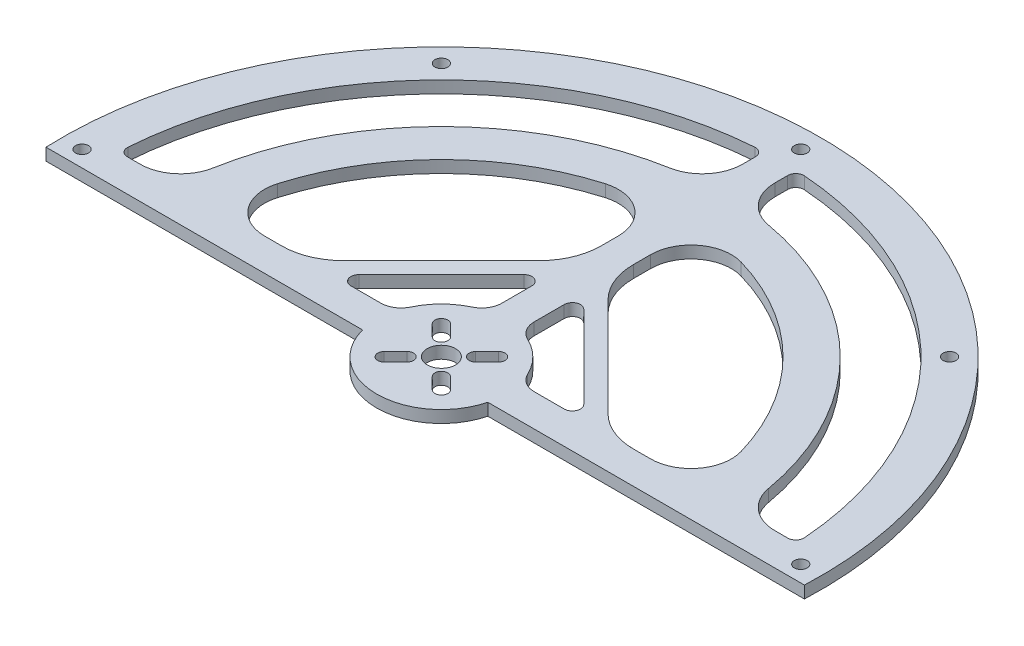
SolidWorks part; units mm, degrees
ref_plane "前视基准面" through (0, 0, 0) normal (0, 0, 1) x (1, 0, 0)
ref_plane "上视基准面" through (0, 0, 0) normal (0, 1, 0) x (1, 0, 0)
ref_plane "右视基准面" through (0, 0, 0) normal (1, 0, 0) x (0, 0, -1)
other "Configuration Table"
sketch "草图1" plane through (0, 0, 0) normal (0, 1, 0) x (1, 0, 0)
  line L0 (0, 0) -> (93.9, 0) construction
  line L15 (46.95, 4) -> (46.95, -4) construction
  line L16 (46.95, 4) -> (47.7604, 4)
  line L17 (46.95, -4) -> (83.8046, -4)
  line L18 (46.95, 4) -> (43.5008, 4)
  line L19 (46.95, -4) -> (15.4919, -4)
  line L20 (-46.95, -4) -> (-15.4919, -4)
  line L21 (-46.95, 4) -> (-43.5008, 4)
  line L22 (-46.95, 4) -> (-47.7604, 4)
  line L23 (-46.95, -4) -> (-83.8046, -4)
  line L24 (-78.5319, 4) -> (-81.6799, 4)
  line L25 (83.8046, -4) -> (93.8148, -4)
  line L26 (-4, 78.5319) -> (-4, 81.6799)
  line L27 (-83.8046, -4) -> (-93.8148, -4)
  line L28 (-4, 46.95) -> (-4, 43.5008)
  line L29 (4, 46.95) -> (4, 43.5008)
  line L30 (-4, 46.95) -> (-4, 47.7604)
  line L31 (4, 46.95) -> (4, 47.7604)
  line L32 (4, 78.5319) -> (4, 81.6799)
  line L33 (-27.8068, 7.4142) -> (-7.4142, 27.8068)
  line L34 (78.5319, 4) -> (81.6799, 4)
  line L35 (4, 83.8046) -> (4, 88.81) [skipped]
  line L36 (27.8068, 7.4142) -> (7.4142, 27.8068)
  line L38 (-32.7805, 8.4405) -> (-8.4405, 32.7805)
  line L40 (32.7805, 8.4405) -> (8.4405, 32.7805)
  line L41 (-4, 26.3925) -> (-4, 18.9737)
  line L42 (4, 26.3925) -> (4, 18.9737)
  line L43 (26.3925, 4) -> (18.9737, 4)
  line L44 (-26.3925, 4) -> (-18.9737, 4)
  line L45 (7.0711, -7.0711) -> (4.2426, -4.2426) construction
  line L46 (5.9397, -8.2024) -> (3.1113, -5.374)
  line L47 (8.2024, -5.9397) -> (5.374, -3.1113)
  line L51 (-7.0711, -7.0711) -> (-4.2426, -4.2426) construction
  line L52 (-8.2024, -5.9397) -> (-5.374, -3.1113)
  line L53 (-5.9397, -8.2024) -> (-3.1113, -5.374)
  line L57 (-7.0711, 7.0711) -> (-4.2426, 4.2426) construction
  line L58 (-5.9397, 8.2024) -> (-3.1113, 5.374)
  line L59 (-8.2024, 5.9397) -> (-5.374, 3.1113)
  line L63 (7.0711, 7.0711) -> (4.2426, 4.2426) construction
  line L64 (8.2024, 5.9397) -> (5.374, 3.1113)
  line L65 (5.9397, 8.2024) -> (3.1113, 5.374)
  arc A2 (64.6464, -4) -> (-64.6464, -4) centre (0, 0) ccw construction
  arc A3 (88.81, -4) -> (-88.81, -4) centre (0, 0) ccw construction
  arc A7 (93.8148, -4) -> (-93.8148, -4) centre (0, 0) ccw
  arc A8 (-15.4919, -4) -> (15.4919, -4) centre (0, 0) ccw
  circle A9 centre (0, 0) radius 8 construction
  arc A20 (14.4561, 6.8571) -> (6.8571, 14.4561) centre (0, 0) ccw
  arc A21 (57.3566, 16.8129) -> (16.8129, 57.3566) centre (0, 0) ccw
  arc A22 (68.6871, 12.245) -> (12.245, 68.6871) centre (0, 0) ccw
  arc A23 (83.6745, 6.1465) -> (6.1465, 83.6745) centre (0, 0) ccw
  arc A24 (-6.1465, 83.6745) -> (-83.6745, 6.1465) centre (0, 0) ccw
  arc A25 (-12.245, 68.6871) -> (-68.6871, 12.245) centre (0, 0) ccw
  arc A26 (-16.8129, 57.3566) -> (-57.3566, 16.8129) centre (0, 0) ccw
  arc A27 (-6.8571, 14.4561) -> (-14.4561, 6.8571) centre (0, 0) ccw
  circle A28 centre (88.9, 0) radius 1.6
  circle A32 centre (-88.9, 0) radius 1.6
  circle A33 centre (-62.8618, 62.8618) radius 1.6
  circle A34 centre (0, 88.9) radius 1.6
  circle A35 centre (62.8618, 62.8618) radius 1.6
  arc A36 (5.9397, -8.2024) -> (8.2024, -5.9397) centre (7.0711, -7.0711) ccw
  arc A37 (5.374, -3.1113) -> (3.1113, -5.374) centre (4.2426, -4.2426) ccw
  arc A40 (-8.2024, -5.9397) -> (-5.9397, -8.2024) centre (-7.0711, -7.0711) ccw
  arc A41 (-3.1113, -5.374) -> (-5.374, -3.1113) centre (-4.2426, -4.2426) ccw
  arc A44 (-5.9397, 8.2024) -> (-8.2024, 5.9397) centre (-7.0711, 7.0711) ccw
  arc A45 (-5.374, 3.1113) -> (-3.1113, 5.374) centre (-4.2426, 4.2426) ccw
  arc A48 (8.2024, 5.9397) -> (5.9397, 8.2024) centre (7.0711, 7.0711) ccw
  arc A49 (3.1113, 5.374) -> (5.374, 3.1113) centre (4.2426, 4.2426) ccw
  arc A50 (16.8129, 57.3566) -> (4, 47.7604) centre (14, 47.7604) ccw
  arc A51 (-4, 47.7604) -> (-16.8129, 57.3566) centre (-14, 47.7604) ccw
  arc A52 (57.3566, 16.8129) -> (47.7604, 4) centre (47.7604, 14) cw
  arc A53 (-47.7604, 4) -> (-57.3566, 16.8129) centre (-47.7604, 14) cw
  arc A54 (8.4405, 32.7805) -> (4, 43.5008) centre (19.1608, 43.5008) cw
  arc A55 (43.5008, 4) -> (32.7805, 8.4405) centre (43.5008, 19.1608) cw
  arc A56 (-8.4405, 32.7805) -> (-4, 43.5008) centre (-19.1608, 43.5008) ccw
  arc A57 (-32.7805, 8.4405) -> (-43.5008, 4) centre (-43.5008, 19.1608) cw
  arc A58 (78.5319, 4) -> (68.6871, 12.245) centre (78.5319, 14) cw
  arc A59 (4, 78.5319) -> (12.245, 68.6871) centre (14, 78.5319) ccw
  arc A60 (-4, 78.5319) -> (-12.245, 68.6871) centre (-14, 78.5319) cw
  arc A61 (-68.6871, 12.245) -> (-78.5319, 4) centre (-78.5319, 14) cw
  arc A62 (-81.6799, 4) -> (-83.6745, 6.1465) centre (-81.6799, 6) cw
  arc A63 (-4, 81.6799) -> (-6.1465, 83.6745) centre (-6, 81.6799) ccw
  arc A64 (4, 81.6799) -> (6.1465, 83.6745) centre (6, 81.6799) cw
  arc A65 (83.6745, 6.1465) -> (81.6799, 4) centre (81.6799, 6) cw
  arc A66 (-6.8571, 14.4561) -> (-4, 18.9737) centre (-9, 18.9737) ccw
  arc A67 (6.8571, 14.4561) -> (4, 18.9737) centre (9, 18.9737) cw
  arc A68 (18.9737, 4) -> (14.4561, 6.8571) centre (18.9737, 9) cw
  arc A69 (-14.4561, 6.8571) -> (-18.9737, 4) centre (-18.9737, 9) cw
  arc A70 (26.3925, 4) -> (27.8068, 7.4142) centre (26.3925, 6) ccw
  arc A71 (-26.3925, 4) -> (-27.8068, 7.4142) centre (-26.3925, 6) cw
  arc A72 (-4, 26.3925) -> (-7.4142, 27.8068) centre (-6, 26.3925) ccw
  arc A73 (7.4142, 27.8068) -> (4, 26.3925) centre (6, 26.3925) ccw
  circle A74 centre (0, 0) radius 3.5
  point P16 (0, 8)
  point P31 (0, -8)
  point P32 (37.221, 4)
  point P38 (-8, 0)
  point P40 (-37.221, 4)
  point P43 (0, 0)
  point P44 (46.95, 0)
  point P47 (46.95, 4)
  point P50 (46.95, -4)
  point P57 (0, 0)
  point P59 (69.6552, 4)
  point P71 (0, 0)
  point P79 (4, 69.6552)
  point P84 (-4, 69.6552)
  point P86 (5.6569, -5.6569)
  point P99 (0, 0)
  point P102 (-69.6552, 4)
  point P109 (-5.6569, -5.6569)
  point P123 (-5.6569, 5.6569)
  point P131 (15.4919, 4)
  point P137 (5.6569, 5.6569)
  point P142 (0, 0)
  point P144 (31.221, 4)
  point P147 (-31.221, 4)
  dimension "D2" = 10
  dimension "D3" = 6
  dimension "D4" = 6
  dimension "D5" = 3.2
  dimension "D6" = 15.1608
  dimension "D7" = 32
  dimension "D8" = 16
  dimension "D9" = 10
  dimension "D12" = 2
  dimension "D13" = 5
  dimension "D14" = 2
  dimension "D15" = 7
  dimension "D10" = 2
  dimension "D11" = 2
extrude "凸台-拉伸1" add sketch "草图1" along normal blind 3
